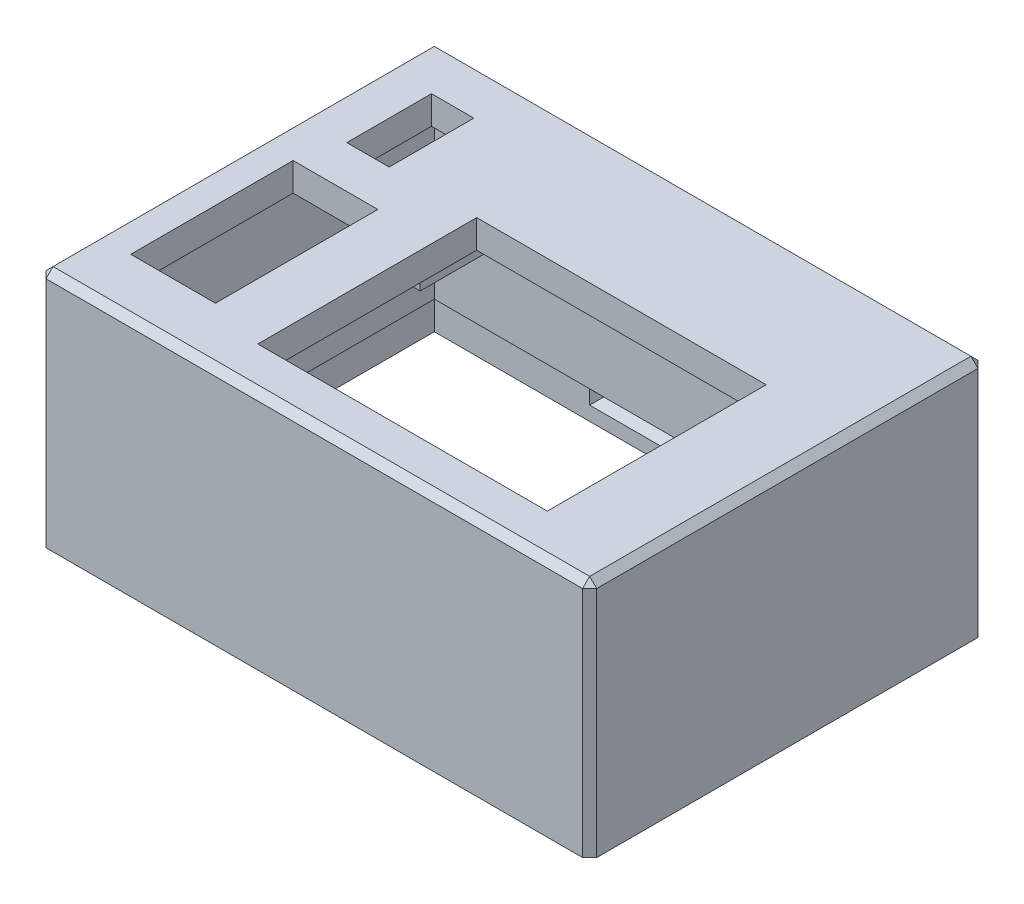
SolidWorks part; units mm, degrees
ref_plane "Спереди" through (0, 0, 0) normal (0, 0, 1) x (1, 0, 0)
ref_plane "Сверху" through (0, 0, 0) normal (0, 1, 0) x (1, 0, 0)
ref_plane "Справа" through (0, 0, 0) normal (1, 0, 0) x (0, 0, -1)
other "Configuration Table"
sketch "Эскиз1" plane through (0, 0, 0) normal (0, 1, 0) x (1, 0, 0)
  line L0 (-22.75, 17.25) -> (16.25, 17.25)
  line L1 (-10.25, -7.75) -> (10.25, -7.75) construction
  line L2 (-10.25, -7.75) -> (-10.25, 7.75) construction
  line L3 (-10.25, 7.75) -> (10.25, 7.75) construction
  line L4 (10.25, -7.75) -> (10.25, 7.75) construction
  line L5 (-10.25, -7.75) -> (10.25, 7.75) construction
  line L6 (-10.25, 7.75) -> (10.25, -7.75) construction
  line L7 (-20.75, 15.25) -> (14.25, 15.25) construction
  line L8 (-20.75, 15.25) -> (-20.75, -8.75) construction
  line L9 (-20.75, -8.75) -> (14.25, -8.75) construction
  line L10 (14.25, 15.25) -> (14.25, -8.75) construction
  line L11 (16.25, 17.25) -> (16.25, -10.75)
  line L12 (-22.75, -10.75) -> (16.25, -10.75)
  line L13 (-22.75, 17.25) -> (-22.75, -10.75)
  point P0 (0, 0)
  dimension "D1" = 20.5
  dimension "D2" = 15.5
  dimension "D3" = 1
  dimension "D4" = 4
  dimension "D5" = 24
  dimension "D6" = 35
  dimension "D7" = 2
extrude "Бобышка-Вытянуть1" add sketch "Эскиз1" along normal blind 17
sketch "Эскиз2" plane through (0, 0, 0) normal (0, 1, 0) x (1, 0, 0)
  line L0 (10.25, -7.75) -> (10.25, 7.75) construction
  line L1 (-10.25, -7.75) -> (10.25, -7.75) construction
  line L2 (-10.25, 7.75) -> (10.25, 7.75) construction
  line L3 (-10.25, -7.75) -> (-10.25, 7.75) construction
  line L4 (10.25, -7.75) -> (10.25, 7.75)
  line L5 (-10.25, -7.75) -> (10.25, -7.75)
  line L6 (-10.25, 7.75) -> (10.25, 7.75)
  line L7 (-10.25, -7.75) -> (-10.25, 7.75)
extrude "Вырез-Вытянуть1" cut sketch "Эскиз2" along normal through all
sketch "Эскиз3" plane through (0, 0, 0) normal (0, 1, 0) x (1, 0, 0)
  line L0 (14.25, 15.25) -> (14.25, -8.75) construction
  line L1 (-20.75, 15.25) -> (-20.75, -8.75) construction
  line L2 (-20.75, 15.25) -> (14.25, 15.25) construction
  line L3 (-20.75, -8.75) -> (14.25, -8.75) construction
  line L4 (14.25, 15.25) -> (14.25, -8.75)
  line L5 (-20.75, 15.25) -> (-20.75, -8.75)
  line L6 (-20.75, 15.25) -> (14.25, 15.25)
  line L7 (-20.75, -8.75) -> (14.25, -8.75)
extrude "Вырез-Вытянуть2" cut sketch "Эскиз3" along normal blind 15
sketch "Эскиз5" plane through (0, 0, 0) normal (0, 1, 0) x (1, 0, 0)
  line L0 (-20.75, -8.75) -> (14.25, -8.75) construction
  line L1 (-20.25, 4.75) -> (-14.25, 4.75)
  line L2 (-20.25, 4.75) -> (-20.25, -6.75)
  line L3 (-20.25, -6.75) -> (-14.25, -6.75)
  line L4 (-14.25, 4.75) -> (-14.25, -6.75)
  line L5 (-20.75, 15.25) -> (-20.75, -8.75) construction
  dimension "D1" = 2
  dimension "D2" = 11.5
  dimension "D3" = 6
  dimension "D4" = 0.5
extrude "Вырез-Вытянуть4" cut sketch "Эскиз5" along normal through all
sketch "Эскиз7" plane through (0, 0, 0) normal (0, 1, 0) x (1, 0, 0)
  line L0 (-20.75, 15.25) -> (14.25, 15.25) construction
  line L1 (-19.45, 13.75) -> (-16.45, 13.75)
  line L2 (-19.45, 13.75) -> (-19.45, 7.75)
  line L3 (-19.45, 7.75) -> (-16.45, 7.75)
  line L4 (-16.45, 13.75) -> (-16.45, 7.75)
  line L5 (-20.75, 15.25) -> (-20.75, -8.75) construction
  dimension "D1" = 3
  dimension "D2" = 6
  dimension "D3" = 1.5
  dimension "D4" = 1.3
extrude "Вырез-Вытянуть5" cut sketch "Эскиз7" along normal through all
sketch "Эскиз6" plane through (0, 15, 0) normal (0, -1, 0) x (1, 0, 0)
  line L0 (-20.75, -15.25) -> (14.25, -15.25) construction
  line L1 (14.25, -15.25) -> (11.75, -15.25)
  line L2 (14.25, -15.25) -> (14.25, -7.25)
  line L3 (14.25, -7.25) -> (11.75, -7.25)
  line L4 (11.75, -15.25) -> (11.75, -7.25)
  line L5 (14.25, 8.75) -> (11.75, 8.75)
  line L6 (14.25, 8.75) -> (14.25, 6.25)
  line L7 (14.25, 6.25) -> (11.75, 6.25)
  line L8 (11.75, 8.75) -> (11.75, 6.25)
  line L9 (-20.75, 8.75) -> (-12.75, 8.75)
  line L10 (-20.75, 8.75) -> (-20.75, 7.55)
  line L11 (-20.75, 7.55) -> (-12.75, 7.55)
  line L12 (-12.75, 8.75) -> (-12.75, 7.55)
  line L13 (-15.75, -7.25) -> (-13.75, -7.25)
  line L14 (-15.75, -7.25) -> (-15.75, -15.25)
  line L15 (-15.75, -15.25) -> (-13.75, -15.25)
  line L16 (-13.75, -7.25) -> (-13.75, -15.25)
  line L17 (-20.75, -15.25) -> (-20.75, 8.75) construction
  dimension "D1" = 2.5
  dimension "D2" = 8
  dimension "D3" = 2
  dimension "D4" = 1.2
  dimension "D5" = 8
  dimension "D6" = 8
  dimension "D7" = 5
extrude "Бобышка-Вытянуть2" add sketch "Эскиз6" along normal blind 4
sketch "Эскиз8" plane through (0, 0, 0) normal (0, 1, 0) x (1, 0, 0)
  line L0 (-21.75, 16.25) -> (-21.75, -9.75)
  line L1 (-22.75, 17.25) -> (16.25, 17.25) construction
  line L2 (-22.75, 17.25) -> (-22.75, -10.75) construction
  line L3 (-22.75, -10.75) -> (16.25, -10.75) construction
  line L4 (16.25, 17.25) -> (16.25, -10.75) construction
  line L5 (-22.75, 17.25) -> (16.25, -10.75) construction
  line L6 (-22.75, -10.75) -> (16.25, 17.25) construction
  line L7 (-21.75, -9.75) -> (15.25, -9.75)
  line L8 (15.25, 16.25) -> (15.25, -9.75)
  line L9 (-21.75, 16.25) -> (15.25, 16.25)
  point P4 (-3.25, 3.25)
extrude "Вырез-Вытянуть6" cut sketch "Эскиз8" along normal blind 3
ref_plane "Плоскость1" through (0, 0, -3.25) normal (0, 0, -1) x (-1, 0, 0)
sketch "Эскиз9" plane through (0, 0, -16.25) normal (0, 0, 1) x (1, 0, 0)
  line L0 (-21.75, 3) -> (15.25, 3) construction
  line L1 (-10.75, 3) -> (4.25, 3)
  line L2 (-10.75, 3) -> (-10.75, 1)
  line L3 (-10.75, 1) -> (4.25, 1)
  line L4 (4.25, 3) -> (4.25, 1)
  line L5 (-10.75, 3) -> (4.25, 1) construction
  line L6 (-10.75, 1) -> (4.25, 3) construction
  line L7 (-3.25, 5.0525) -> (-3.25, -1.2778) construction
  line L9 (-22.75, 17) -> (-22.75, 0) construction
  line L10 (16.25, 17) -> (16.25, 0) construction
  point P4 (-3.25, 2)
  point P9 (0, 0)
  dimension "D1" = 15
  dimension "D2" = 2
extrude "Вырез-Вытянуть7" cut sketch "Эскиз9" against normal blind 0.5 draft 45
mirror "Зеркальное отражение1" about plane through (0, 0, -3.25) normal (0, 0, -1) of "Вырез-Вытянуть7"
sketch "Эскиз12" plane through (0, 0, -17.25) normal (0, 0, -1) x (-1, 0, 0)
  line L1 (-10.25, 14.2) -> (-6.25, 14.2)
  line L2 (-10.25, 14.2) -> (-10.25, 11.7)
  line L3 (-10.25, 11.7) -> (-6.25, 11.7)
  line L4 (-6.25, 14.2) -> (-6.25, 11.7)
  line L5 (-10.25, 14.2) -> (-6.25, 11.7) construction
  line L6 (-10.25, 11.7) -> (-6.25, 14.2) construction
  line L8 (-14.25, 11) -> (-14.25, 3) construction
  line L9 (-11.75, 11) -> (-14.25, 11) construction
  point P4 (-8.25, 12.95)
  dimension "D1" = 4
  dimension "D2" = 2.5
  dimension "D3" = 0.7
  dimension "D4" = 4
extrude "Вырез-Вытянуть8" cut sketch "Эскиз12" against normal up to next
chamfer "Фаска1" distance 0.5 angle 45 8 edges at (-22.75, 8.5, -17.25) (-22.75, 8.5, 10.75) (16.25, 8.5, 10.75) (16.25, 8.5, -17.25) (16.25, 17, -3.25) (-3.25, 17, -17.25) (-22.75, 17, -3.25) (-3.25, 17, 10.75)
sketch "Эскиз13" plane through (0, 0, 0) normal (0, 1, 0) x (1, 0, 0)
  line L0 (10.25, 15.25) -> (10.25, 17.25) construction
  line L1 (6.25, 15.25) -> (10.25, 15.25)
  line L2 (6.25, 15.25) -> (6.25, 16.25)
  line L3 (6.25, 16.25) -> (10.25, 16.25)
  line L4 (10.25, 15.25) -> (10.25, 16.25)
  line L5 (6.25, 15.25) -> (10.25, 16.25) construction
  line L6 (6.25, 16.25) -> (10.25, 15.25) construction
  point P4 (8.25, 15.75)
extrude "Вырез-Вытянуть9" cut sketch "Эскиз13" along normal up to surface (11.7 mm away) up to face at (8.25, 11.7, -16.25)
